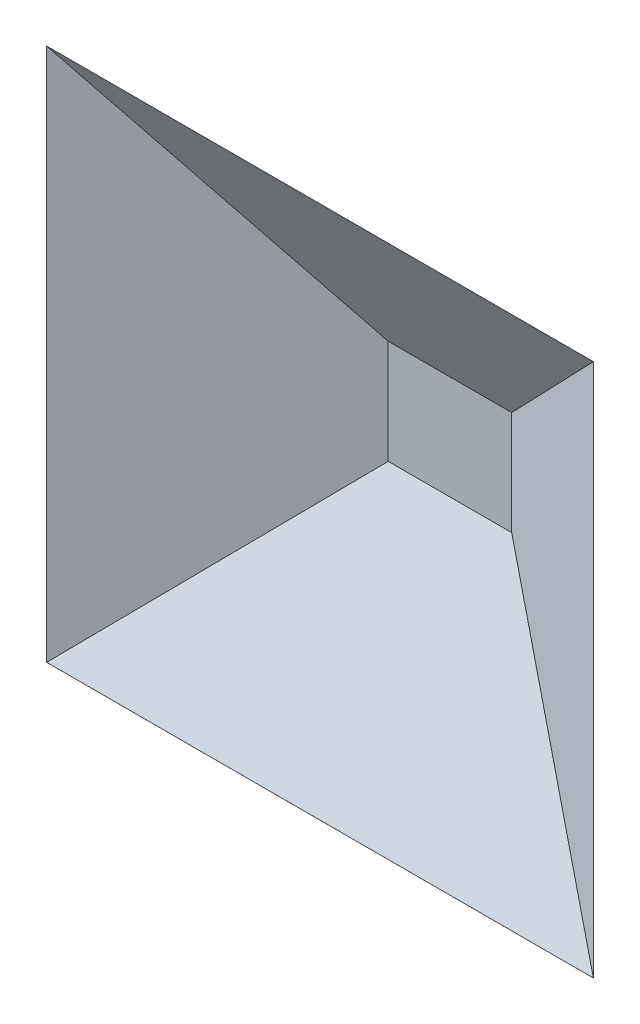
SolidWorks part; units mm, degrees
ref_plane "前视基准面" through (0, 0, 0) normal (0, 0, 1) x (1, 0, 0)
ref_plane "上视基准面" through (0, 0, 0) normal (0, 1, 0) x (1, 0, 0)
ref_plane "右视基准面" through (0, 0, 0) normal (1, 0, 0) x (0, 0, -1)
sketch "草图2" plane through (0, 0, 0) normal (1, 0, 0) x (0, 0, -1)
  line L0 (-100, 87.4251) -> (-100, -64.6707)
  dimension "D1" = 100
surface "曲面-拉伸1" sketch "草图2" parameters "D1"=10
sketch "草图3" plane through (0, 0, 0) normal (0, 0, 1) x (1, 0, 0)
  line L1 (-47.5, 40) -> (47.5, 40)
  line L2 (-47.5, 40) -> (-47.5, -40)
  line L3 (-47.5, -40) -> (47.5, -40)
  line L4 (47.5, 40) -> (47.5, -40)
  line L5 (-47.5, 40) -> (47.5, -40) construction
  line L6 (-47.5, -40) -> (47.5, 40) construction
  point P0 (0, 0)
  dimension "D1" = 95
  dimension "D2" = 80
sketch "草图4" plane through (0, 0, 100) normal (0, 0, 1) x (1, 0, 0)
  line L1 (-210.3, 205.3) -> (210.3, 205.3)
  line L2 (-210.3, 205.3) -> (-210.3, -205.3)
  line L3 (-210.3, -205.3) -> (210.3, -205.3)
  line L4 (210.3, 205.3) -> (210.3, -205.3)
  line L5 (-210.3, 205.3) -> (210.3, -205.3) construction
  line L6 (-210.3, -205.3) -> (210.3, 205.3) construction
  point P0 (0, 0)
  dimension "D1" = 420.6
  dimension "D2" = 410.6
loft "放样1" add profiles "草图3", "草图4"
shell "抽壳1" thickness 0.01
